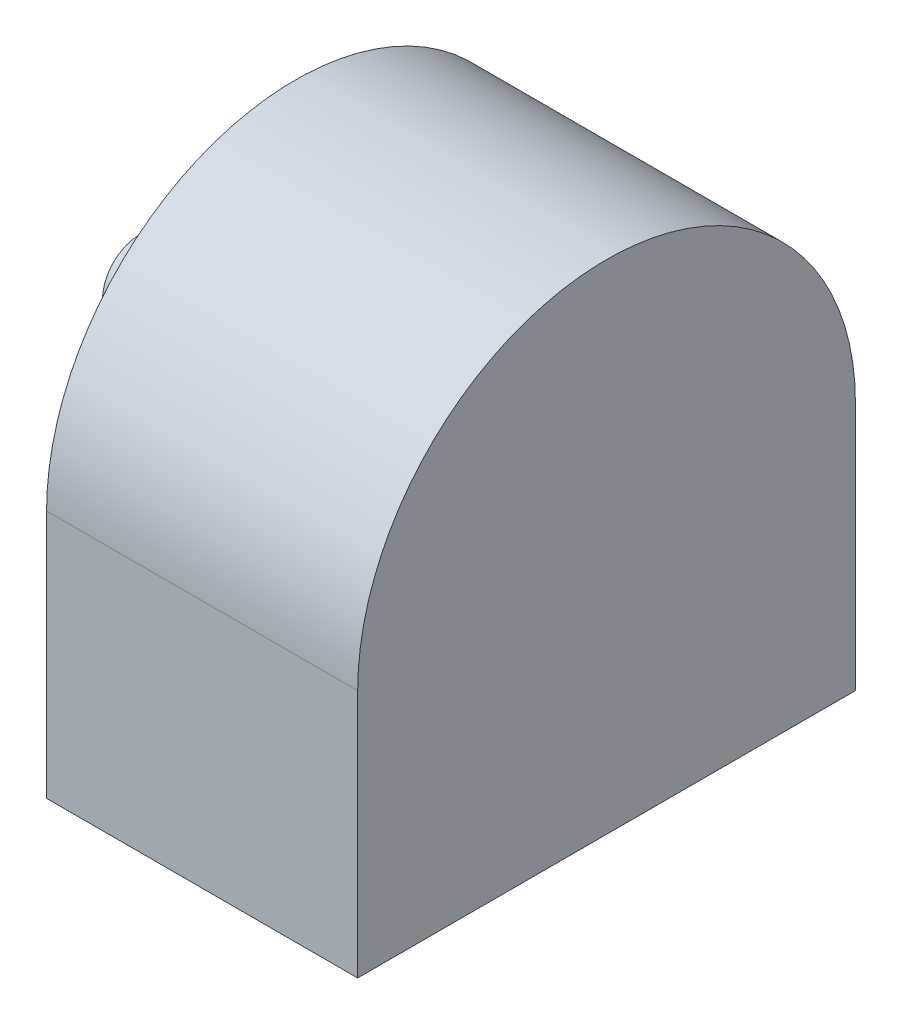
SolidWorks part; units mm, degrees
ref_plane "Front Plane" through (0, 0, 0) normal (0, 0, 1) x (1, 0, 0)
ref_plane "Top Plane" through (0, 0, 0) normal (0, 1, 0) x (1, 0, 0)
ref_plane "Right Plane" through (0, 0, 0) normal (1, 0, 0) x (0, 0, -1)
sketch "Sketch1" plane through (0, 0, 0) normal (0, 0, 1) x (1, 0, 0)
  line L0 (0, 0) -> (-150, 0)
  line L1 (-150, 0) -> (-150, 12)
  line L2 (-150, 12) -> (-100, 12)
  line L3 (-100, 12) -> (-100, 80)
  line L4 (-100, 80) -> (0, 80)
  line L5 (0, 80) -> (0, 0)
  dimension "D1" = 12
  dimension "D2" = 50
  dimension "D3" = 80
  dimension "D4" = 100
revolve "Revolve1" add sketch "Sketch1" angle 360 about L0
sketch "Sketch3" plane through (0, 0, 0) normal (1, 0, 0) x (0, 0, -1)
  line L1 (-80, 0) -> (80, 0)
  line L2 (-80, 0) -> (-80, -80)
  line L3 (-80, -80) -> (80, -80)
  line L4 (80, 0) -> (80, -80)
  circle A0 centre (0, 0) radius 80 construction
extrude "Boss-Extrude1" add sketch "Sketch3" against normal up to surface (100 mm away) up to face at (-100, 12, 0)
sketch "Sketch5" plane through (0, -80, 0) normal (0, -1, 0) x (1, 0, 0)
  line L0 (-50, 80) -> (-50, -80) construction
  line L1 (-100, 80) -> (0, 80) construction
  line L2 (-100, -80) -> (0, -80) construction
  line L3 (-100, 0) -> (0, 0) construction
  line L4 (-100, 80) -> (-100, -80) construction
  circle A0 centre (-50, 54.6948) radius 12.5
  circle A1 centre (-50, -65.3052) radius 12.5
  dimension "D1" = 25
  dimension "D2" = 120
extrude "Cut-Extrude2" cut sketch "Sketch5" against normal blind 50
